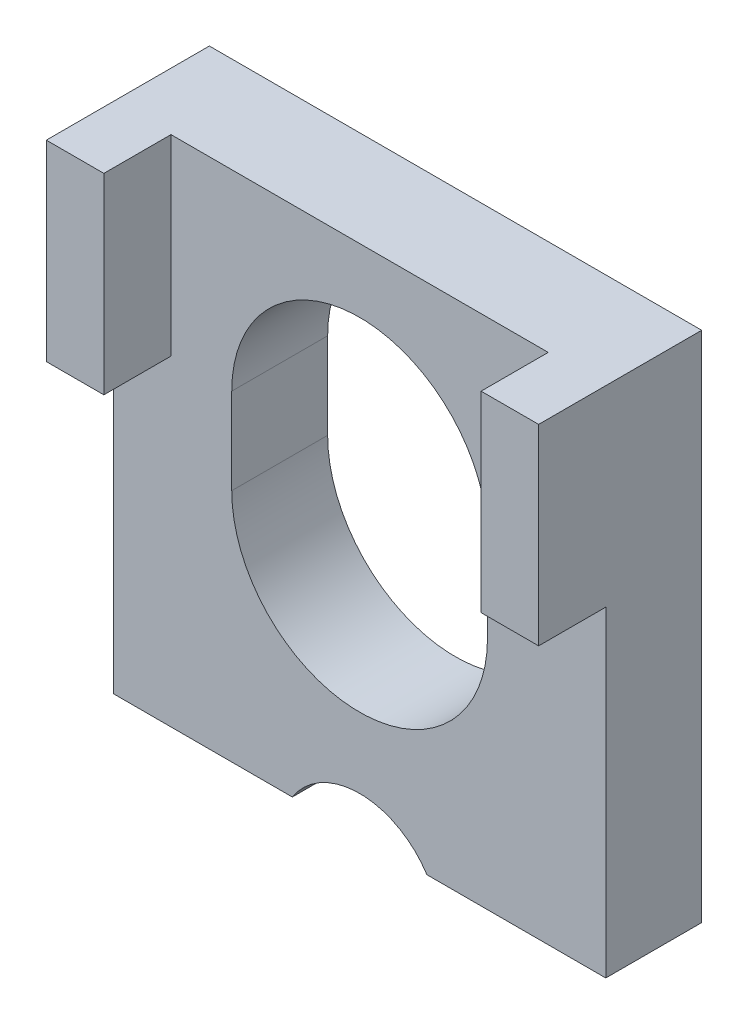
SolidWorks part; units mm, degrees
ref_plane "Спереди" through (0, 0, 0) normal (0, 0, 1) x (1, 0, 0)
ref_plane "Сверху" through (0, 0, 0) normal (0, 1, 0) x (1, 0, 0)
ref_plane "Справа" through (0, 0, 0) normal (1, 0, 0) x (0, 0, -1)
sketch "Эскиз1" plane through (0, 0, 0) normal (0, 0, 1) x (1, 0, 0)
  line L1 (-7.7, 13.7375) -> (7.7, 13.7375)
  line L5 (-7.7, 13.7375) -> (-7.7, -0.0396)
  line L6 (7.7, 13.7375) -> (7.7, -0.0396)
  line L7 (-7.7, -0.0396) -> (-7.7, -2.3094)
  line L8 (-7.7, -2.3094) -> (-2.1044, -2.3094)
  line L9 (0, 7.7375) -> (0, 5.041) construction
  line L10 (4, 7.7375) -> (4, 5.041)
  line L11 (-4, 7.7375) -> (-4, 5.041)
  line L12 (7.7, -0.0396) -> (7.7, -2.3094)
  line L13 (7.7, -2.3094) -> (2.1044, -2.3094)
  arc A0 (-2.1044, -2.3094) -> (2.1044, -2.3094) centre (0, -3.659) cw
  arc A1 (4, 7.7375) -> (-4, 7.7375) centre (0, 7.7375) ccw
  arc A2 (-4, 5.041) -> (4, 5.041) centre (0, 5.041) ccw
  point P1 (0, 6.3893)
  point P15 (0, 11.7375)
  point P16 (0, 1.041)
  dimension "D1" = 2.5
  dimension "D5" = 4
  dimension "D4" = 2.2
  dimension "D2" = 15.4
  dimension "D3" = 7.7
  dimension "D6" = 10.6965
  dimension "D7" = 2
  dimension "D8" = 7.7
extrude "Бобышка-Вытянуть1" add sketch "Эскиз1" along normal blind 3
sketch "Эскиз2" plane through (0, 0, 3) normal (0, 0, 1) x (1, 0, 0)
  line L1 (-7.7, 13.7375) -> (-5.9, 13.7375)
  line L2 (-7.7, 13.7375) -> (-7.7, 7.7375)
  line L3 (-7.7, 7.7375) -> (-5.9, 7.7375)
  line L4 (-5.9, 13.7375) -> (-5.9, 7.7375)
  line L5 (7.7, 13.7375) -> (5.9, 13.7375)
  line L6 (7.7, 13.7375) -> (7.7, 7.7375)
  line L7 (7.7, 7.7375) -> (5.9, 7.7375)
  line L8 (5.9, 13.7375) -> (5.9, 7.7375)
  dimension "D1" = 1.8
  dimension "D2" = 1.8
  dimension "D3" = 6
  dimension "D4" = 6
extrude "Бобышка-Вытянуть2" add sketch "Эскиз2" along normal blind 2.1
